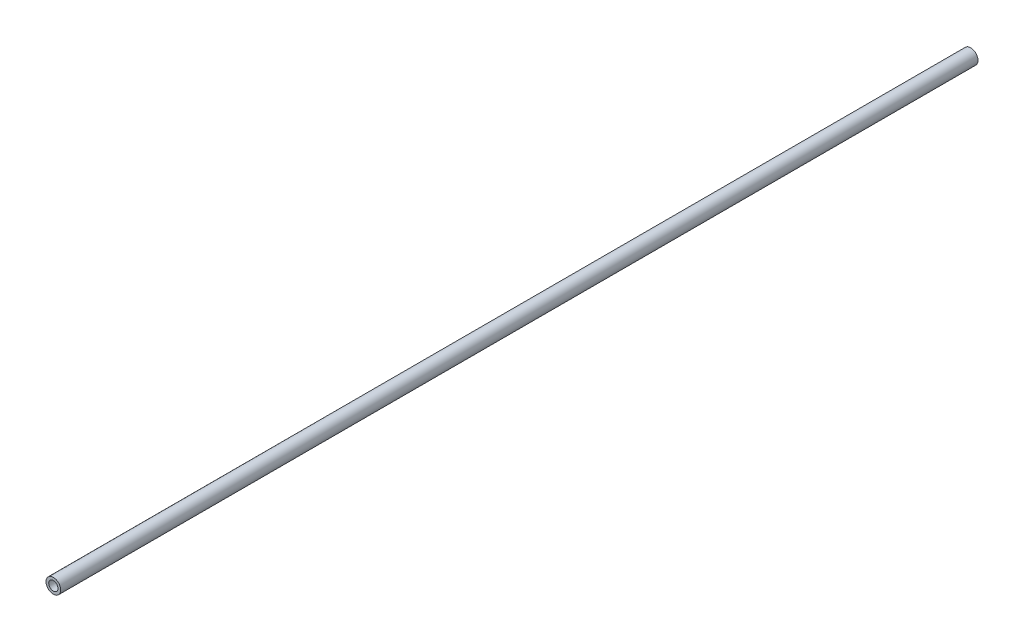
SolidWorks part; units mm, degrees
ref_plane "Front Plane" through (0, 0, 0) normal (0, 0, 1) x (1, 0, 0)
ref_plane "Top Plane" through (0, 0, 0) normal (0, 1, 0) x (1, 0, 0)
ref_plane "Right Plane" through (0, 0, 0) normal (1, 0, 0) x (0, 0, -1)
sketch "Sketch1" plane through (0, 0, 0) normal (0, 0, 1) x (1, 0, 0)
  circle A0 centre (0, 0) radius 2.3876
  circle A1 centre (0, 0) radius 1.4986
  dimension "D1" = 4.7752
  dimension "D2" = 2.9972
extrude "Boss-Extrude1" add sketch "Sketch1" along normal blind 298.45
